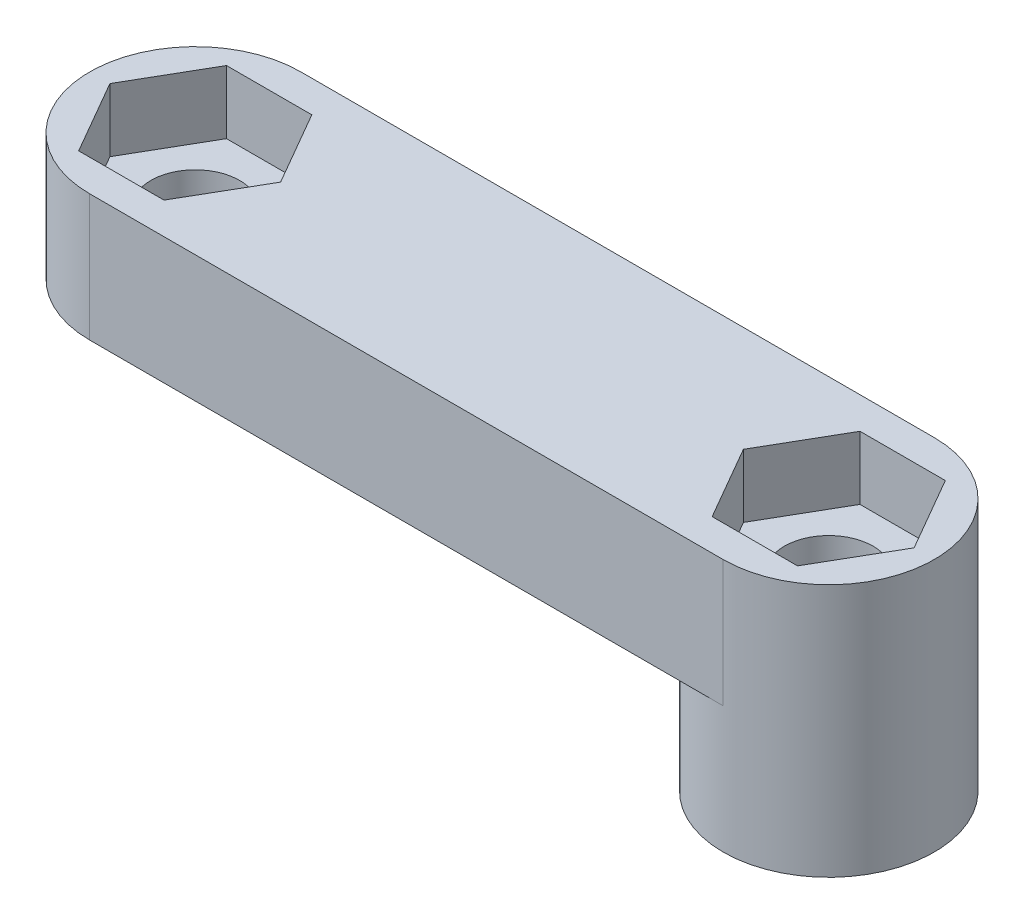
SolidWorks part; units mm, degrees
ref_plane "Front Plane" through (0, 0, 0) normal (0, 0, 1) x (1, 0, 0)
ref_plane "Top Plane" through (0, 0, 0) normal (0, 1, 0) x (1, 0, 0)
ref_plane "Right Plane" through (0, 0, 0) normal (1, 0, 0) x (0, 0, -1)
sketch "Sketch1" plane through (0, 0, 0) normal (0, 1, 0) x (1, 0, 0)
  line L0 (-15, 0) -> (15, 0) construction
  line L1 (-15, 5) -> (15, 5)
  line L2 (-15, -5) -> (15, -5)
  arc A0 (-15, 5) -> (-15, -5) centre (-15, 0) ccw
  arc A1 (15, -5) -> (15, 5) centre (15, 0) ccw
  circle A2 centre (15, 0) radius 2.1
  circle A3 centre (-15, 0) radius 2.1
  point P2 (0, 0)
  dimension "D3" = 4.2
  dimension "D4" = 4.2
  dimension "D1" = 10
  dimension "D2" = 30
extrude "Boss-Extrude1" add sketch "Sketch1" along normal mid plane 6
sketch "Sketch2" plane through (0, 3, 0) normal (0, 1, 0) x (1, 0, 0)
  line L1 (-10.9585, 0) -> (-12.9793, 3.5)
  line L2 (-12.9793, 3.5) -> (-17.0207, 3.5)
  line L3 (-17.0207, 3.5) -> (-19.0415, 0)
  line L4 (-19.0415, 0) -> (-17.0207, -3.5)
  line L5 (-17.0207, -3.5) -> (-12.9793, -3.5)
  line L6 (-12.9793, -3.5) -> (-10.9585, 0)
  line L7 (10.9585, 0) -> (12.9793, -3.5)
  line L8 (12.9793, -3.5) -> (17.0207, -3.5)
  line L9 (17.0207, -3.5) -> (19.0415, 0)
  line L10 (19.0415, 0) -> (17.0207, 3.5)
  line L11 (17.0207, 3.5) -> (12.9793, 3.5)
  line L12 (12.9793, 3.5) -> (10.9585, 0)
  circle A0 centre (-15, 0) radius 3.5 construction
  circle A1 centre (15, 0) radius 3.5 construction
  dimension "D1" = 7
  dimension "D2" = 7
extrude "Cut-Extrude1" cut sketch "Sketch2" against normal blind 3
sketch "Sketch3" plane through (0, -3, 0) normal (0, -1, 0) x (1, 0, 0)
  circle A0 centre (15, 0) radius 2.1
  circle A1 centre (15, 0) radius 5
extrude "Boss-Extrude2" add sketch "Sketch3" along normal blind 6
